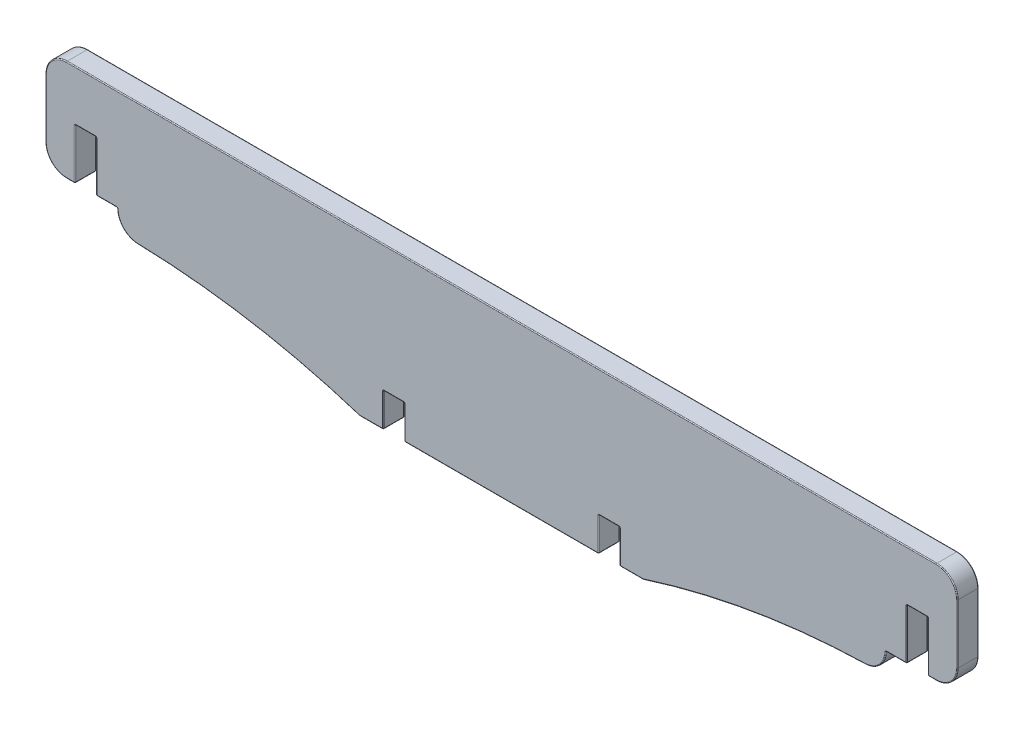
SolidWorks part; units mm, degrees
ref_plane "Plano frontal" through (0, 0, 0) normal (0, 0, 1) x (1, 0, 0)
ref_plane "Plano superior" through (0, 0, 0) normal (0, 1, 0) x (1, 0, 0)
ref_plane "Plano direito" through (0, 0, 0) normal (1, 0, 0) x (0, 0, -1)
sketch "Esboço1" plane through (0, 0, 0) normal (0, 0, 1) x (1, 0, 0)
  line L0 (5.8571, 44.1269) -> (4.8571, 44.1269)
  line L1 (44.8571, 37.1269) -> (67.8571, 37.1269)
  line L2 (101.8571, 41.6269) -> (88.4064, 41.6269) construction
  line L3 (101.8571, 44.1269) -> (101.8571, 44.0945)
  line L4 (104.3571, 44.1269) -> (101.8571, 44.1269)
  line L5 (104.3571, 50.1269) -> (104.3571, 44.1269)
  line L6 (106.8571, 44.1269) -> (104.3571, 44.1269)
  line L7 (106.8571, 50.1269) -> (106.8571, 44.1269)
  line L8 (106.8571, 50.1269) -> (104.3571, 50.1269)
  line L9 (67.8571, 37.1269) -> (67.8571, 41.1269)
  line L10 (70.3571, 41.1269) -> (67.8571, 41.1269)
  line L11 (70.3571, 37.1269) -> (70.3571, 41.1269)
  line L12 (73.157, 37.1269) -> (70.3571, 37.1269)
  line L13 (4.8571, 56.1269) -> (107.8571, 56.1269)
  line L14 (2.3571, 53.6269) -> (2.3571, 46.6269)
  line L15 (39.5571, 37.1269) -> (42.3571, 37.1269)
  line L16 (110.3571, 53.6269) -> (110.3571, 46.6269)
  line L17 (106.8571, 44.1269) -> (107.8571, 44.1269)
  line L18 (42.3571, 37.1269) -> (42.3571, 41.1269)
  line L19 (42.3571, 41.1269) -> (44.8571, 41.1269)
  line L20 (44.8571, 37.1269) -> (44.8571, 41.1269)
  line L25 (5.8571, 50.1269) -> (8.3571, 50.1269)
  line L26 (5.8571, 50.1269) -> (5.8571, 44.1269)
  line L27 (5.8571, 44.1269) -> (8.3571, 44.1269)
  line L28 (8.3571, 50.1269) -> (8.3571, 44.1269)
  line L29 (8.3571, 44.1269) -> (10.8571, 44.1269)
  line L30 (10.8571, 44.1269) -> (10.8571, 44.0945)
  line L31 (10.8571, 41.6269) -> (24.3077, 41.6269) construction
  line L32 (56.3571, 37.1269) -> (56.3571, 56.1269) construction
  arc A0 (101.8571, 44.0945) -> (99.422, 41.5953) centre (99.3571, 44.0945) cw
  arc A1 (107.8571, 44.1269) -> (110.3571, 46.6269) centre (107.8571, 46.6269) ccw
  arc A2 (13.2921, 41.5953) -> (39.5571, 37.1269) centre (10.8571, -52.1445) cw
  arc A3 (4.8571, 56.1269) -> (2.3571, 53.6269) centre (4.8571, 53.6269) ccw
  arc A4 (4.8571, 44.1269) -> (2.3571, 46.6269) centre (4.8571, 46.6269) cw
  arc A5 (10.8571, 44.0945) -> (13.2921, 41.5953) centre (13.3571, 44.0945) ccw
  arc A6 (107.8571, 56.1269) -> (110.3571, 53.6269) centre (107.8571, 53.6269) cw
  arc A7 (99.422, 41.5953) -> (73.157, 37.1269) centre (101.8571, -52.1445) ccw
  dimension "D19" = 2.5
  dimension "D20" = 2.5
  dimension "D3" = 54
  dimension "D4" = 11.5
  dimension "D5" = 2.5
  dimension "D13" = 2.5
  dimension "D14" = 6
  dimension "D15" = 6
  dimension "D16" = 2.5
  dimension "D17" = 2.5
  dimension "D18" = 3.5
extrude "Ressalto-extrusão1" add sketch "Esboço1" along normal blind 2.5 contours A7 A0 L3 L4 L5 L8 L7 L17 A1 L16 A6 L13 A3 L14 A4 L0 L26 L25 L28 L29 L30 A5 A2 L15 L18 L19 L20 L1 L9 L10 L11 L12
fillet "Filete1" radius 0.1 4 edges at (5.8571, 50.1269, 1.25) (70.3571, 41.1269, 1.25) (104.3571, 50.1269, 1.25) (106.8571, 50.1269, 1.25)
fillet "Filete2" radius 0.1 4 edges at (101.8571, 44.1269, 1.25) (42.3571, 41.1269, 1.25) (44.8571, 41.1269, 1.25) (67.8571, 41.1269, 1.25)
fillet "Filete3" radius 0.1 2 edges at (10.8571, 44.1269, 1.25) (8.3571, 50.1269, 1.25)
fillet "Filete4" radius 0.1 90 edges at (5.8863, 50.0977, 2.5) (5.8863, 50.0977, 0) (104.3571, 44.1269, 1.25) (106.8571, 44.1269, 1.25) (5.8571, 44.1269, 1.25) (8.3571, 44.1269, 1.25) (39.5571, 37.1269, 1.25) (42.3571, 37.1269, 1.25) (44.8571, 37.1269, 1.25) (67.8571, 37.1269, 1.25) (70.3571, 37.1269, 1.25) (73.157, 37.1269, 1.25) (71.757, 37.1269, 2.5) (70.3571, 39.0769, 2.5) (69.1071, 41.1269, 2.5) (67.8571, 39.0769, 2.5) (56.3571, 37.1269, 2.5) (44.8571, 39.0769, 2.5) (43.6071, 41.1269, 2.5) (42.3571, 39.0769, 2.5) (40.9571, 37.1269, 2.5) (26.5841, 40.2987, 2.5) (11.5893, 42.3267, 2.5) (10.8277, 44.0986, 2.5) (9.5575, 44.1269, 2.5) (8.3571, 47.0769, 2.5) (7.1071, 50.1269, 2.5) (5.8571, 47.0769, 2.5) (5.3571, 44.1269, 2.5) (3.0893, 44.8592, 2.5) (2.3571, 50.1269, 2.5) (3.0893, 55.3947, 2.5) (56.3571, 56.1269, 2.5) (109.6248, 55.3947, 2.5) (110.3571, 50.1269, 2.5) (109.6248, 44.8592, 2.5) (107.3571, 44.1269, 2.5) (106.8571, 47.0769, 2.5) (105.6071, 50.1269, 2.5) (104.3571, 47.0769, 2.5) (103.1566, 44.1269, 2.5) (101.8864, 44.0986, 2.5) (101.1248, 42.3267, 2.5) (86.13, 40.2987, 2.5) (101.1248, 42.3267, 0) (101.8864, 44.0986, 0) (103.1566, 44.1269, 0) (104.3571, 47.0769, 0) (105.6071, 50.1269, 0) (106.8571, 47.0769, 0) (107.3571, 44.1269, 0) (109.6248, 44.8592, 0) (110.3571, 50.1269, 0) (109.6248, 55.3947, 0) (56.3571, 56.1269, 0) (3.0893, 55.3947, 0) (2.3571, 50.1269, 0) (3.0893, 44.8592, 0) (5.3571, 44.1269, 0) (5.8571, 47.0769, 0) (7.1071, 50.1269, 0) (8.3571, 47.0769, 0) (9.5575, 44.1269, 0) (10.8277, 44.0986, 0) (11.5893, 42.3267, 0) (26.5841, 40.2987, 0) (40.9571, 37.1269, 0) (42.3571, 39.0769, 0) (43.6071, 41.1269, 0) (44.8571, 39.0769, 0) (56.3571, 37.1269, 0) (67.8571, 39.0769, 0) (69.1071, 41.1269, 0) (70.3571, 39.0769, 0) (71.757, 37.1269, 0) (86.13, 40.2987, 0) (70.3278, 41.0977, 2.5) (67.8863, 41.0977, 2.5) (44.8278, 41.0977, 2.5) (42.3863, 41.0977, 2.5) (8.3278, 50.0977, 2.5) (106.8278, 50.0977, 2.5) (104.3863, 50.0977, 2.5) (104.3863, 50.0977, 0) (106.8278, 50.0977, 0) (8.3278, 50.0977, 0) (42.3863, 41.0977, 0) (44.8278, 41.0977, 0) (67.8863, 41.0977, 0) (70.3278, 41.0977, 0)
